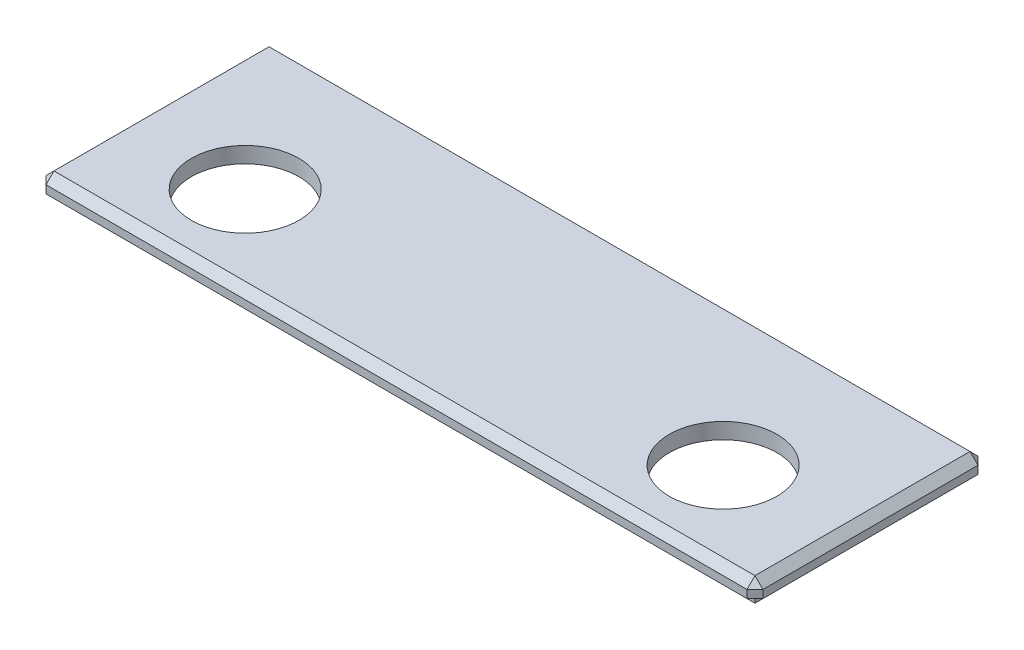
SolidWorks part; units mm, degrees
ref_plane "Front" through (0, 0, 0) normal (0, 0, 1) x (1, 0, 0)
ref_plane "Top" through (0, 0, 0) normal (0, 1, 0) x (1, 0, 0)
ref_plane "Right" through (0, 0, 0) normal (1, 0, 0) x (0, 0, -1)
sketch "Sketch1" plane through (0, 0, 0) normal (0, 1, 0) x (1, 0, 0)
  line L1 (-45, -14.5) -> (45, -14.5)
  line L2 (-45, -14.5) -> (-45, 14.5)
  line L3 (-45, 14.5) -> (45, 14.5)
  line L4 (45, -14.5) -> (45, 14.5)
  line L5 (-45, -14.5) -> (45, 14.5) construction
  line L6 (-45, 14.5) -> (45, -14.5) construction
  point P0 (0, 0)
  point P6 (-45, 14.6784)
  dimension "D1" = 90
  dimension "D2" = 29
extrude "Boss-Extrude1" add sketch "Sketch1" along normal blind 2
chamfer "Chamfer1" distance 1 angle 45 8 edges at (-45, 1, -14.5) (-45, 2, 0) (-45, 1, 14.5) (45, 1, -14.5) (0, 2, -14.5) (45, 2, 0) (45, 1, 14.5) (0, 2, 14.5)
sketch "Sketch2" plane through (0, 2, 0) normal (0, 1, 0) x (1, 0, 0)
  line L0 (-30, -3.5) -> (30, -3.5) construction
  line L2 (-42.5, -12) -> (42.5, -12) construction
  line L3 (-42.5, -12) -> (-42.5, 12) construction
  line L4 (-42.5, 12) -> (42.5, 12) construction
  line L5 (42.5, -12) -> (42.5, 12) construction
  line L6 (-42.5, -12) -> (42.5, 12) construction
  line L7 (-42.5, 12) -> (42.5, -12) construction
  circle A0 centre (-30, -3.5) radius 6.75
  circle A1 centre (30, -3.5) radius 6.75
  point P4 (0, -3.5)
  point P6 (0, 0)
  point P11 (39.6105, 12.1087)
  dimension "D2" = 13.5
  dimension "D1" = 60
  dimension "D3" = 24
  dimension "D4" = 85
  dimension "D5" = 8.5
extrude "Cut-Extrude1" cut sketch "Sketch2" against normal through all
sketch "Sketch3" plane through (0, 0, 0) normal (0, -1, 0) x (1, 0, 0)
  line L0 (-41, 0) -> (-43, 0) construction
  line L1 (-43, -12.5) -> (43, -12.5)
  line L2 (-43, -12.5) -> (-43, 12.5)
  line L3 (-43, 12.5) -> (43, 12.5)
  line L4 (43, -12.5) -> (43, 12.5)
  line L5 (-43, -12.5) -> (43, 12.5) construction
  line L6 (-43, 12.5) -> (43, -12.5) construction
  line L7 (-41, -10.5) -> (41, -10.5)
  line L8 (-41, -10.5) -> (-41, 10.5)
  line L9 (-41, 10.5) -> (41, 10.5)
  line L10 (41, -10.5) -> (41, 10.5)
  line L11 (-41, -10.5) -> (41, 10.5) construction
  line L12 (-41, 10.5) -> (41, -10.5) construction
  line L13 (0, 10.5) -> (0, 12.5) construction
  point P0 (0, 0)
  point P6 (0, 0)
  point P15 (37.8409, -8.4796)
  point P16 (41.4148, -10.9148)
  dimension "D1" = 86
  dimension "D2" = 25
  dimension "D3" = 2
extrude "Boss-Extrude2" add sketch "Sketch3" along normal blind 2
